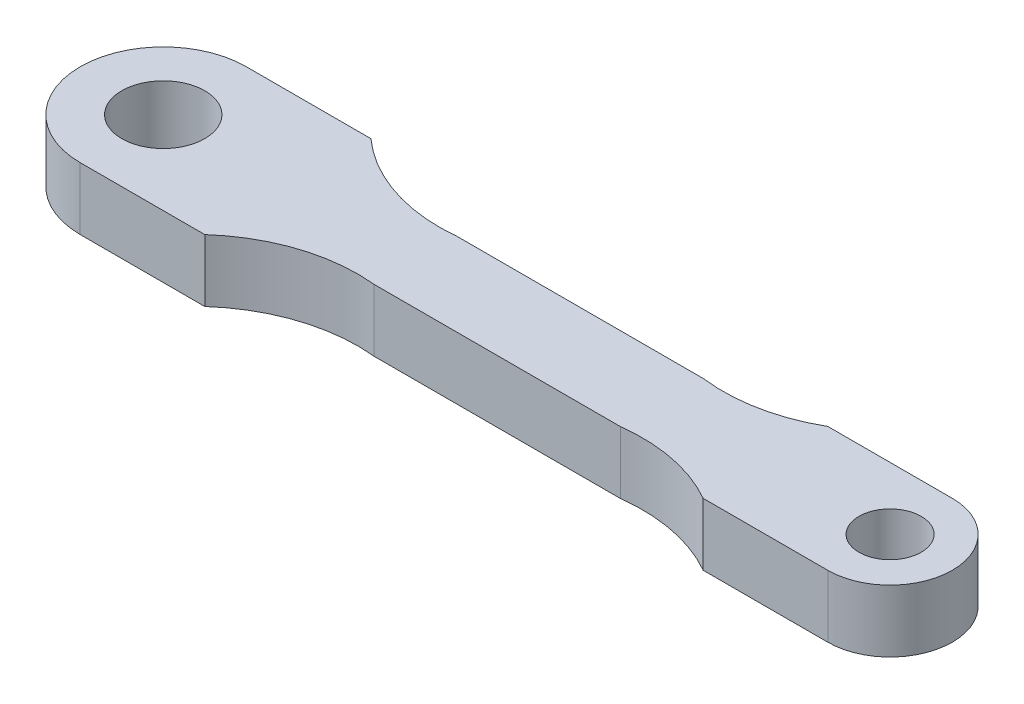
SolidWorks part; units mm, degrees
ref_plane "Front Plane" through (0, 0, 0) normal (0, 0, 1) x (1, 0, 0)
ref_plane "Top Plane" through (0, 0, 0) normal (0, 1, 0) x (1, 0, 0)
ref_plane "Right Plane" through (0, 0, 0) normal (1, 0, 0) x (0, 0, -1)
sketch "Sketch1" plane through (0, 0, 0) normal (0, 1, 0) x (1, 0, 0)
  line L0 (0, 0) -> (-17.5, 0) construction
  line L1 (-17.5, 0) -> (17.5, 0) construction
  line L2 (-17.5, 4) -> (-11.5, 4)
  line L3 (-17.5, -4) -> (-11.5, -4)
  line L4 (17.5, 3) -> (11.5, 3)
  line L5 (17.5, -3) -> (11.5, -3)
  line L6 (-5.3414, 2) -> (6.517, 2)
  line L7 (-5.3414, -2) -> (6.517, -2)
  circle A0 centre (-17.5, 0) radius 4
  circle A1 centre (17.5, 0) radius 3
  arc A2 (6.517, 2) -> (11.5, 3) centre (7.5159, 9.9374) ccw
  arc A3 (6.517, -2) -> (11.5, -3) centre (7.5159, -9.9374) cw
  arc A4 (-11.5, 4) -> (-5.3414, 2) centre (-6.1611, 9.9579) ccw
  arc A5 (-11.5, -4) -> (-5.3414, -2) centre (-6.1611, -9.9579) cw
  circle A6 centre (-17.5, 0) radius 2
  circle A7 centre (17.5, 0) radius 1.5
  dimension "D1" = 8
  dimension "D2" = 6
  dimension "D7" = 8
  dimension "D8" = 8
  dimension "D9" = 4
  dimension "D10" = 3
  dimension "D3" = 35
  dimension "D4" = 6
  dimension "D5" = 6
  dimension "D6" = 4
extrude "Boss-Extrude1" add sketch "Sketch1" along normal mid plane 3 contours L3 A5 L7 A3 L5 A1 L4 A2 L6 A4 L2 A0 | A0 A6 | A1 A7
